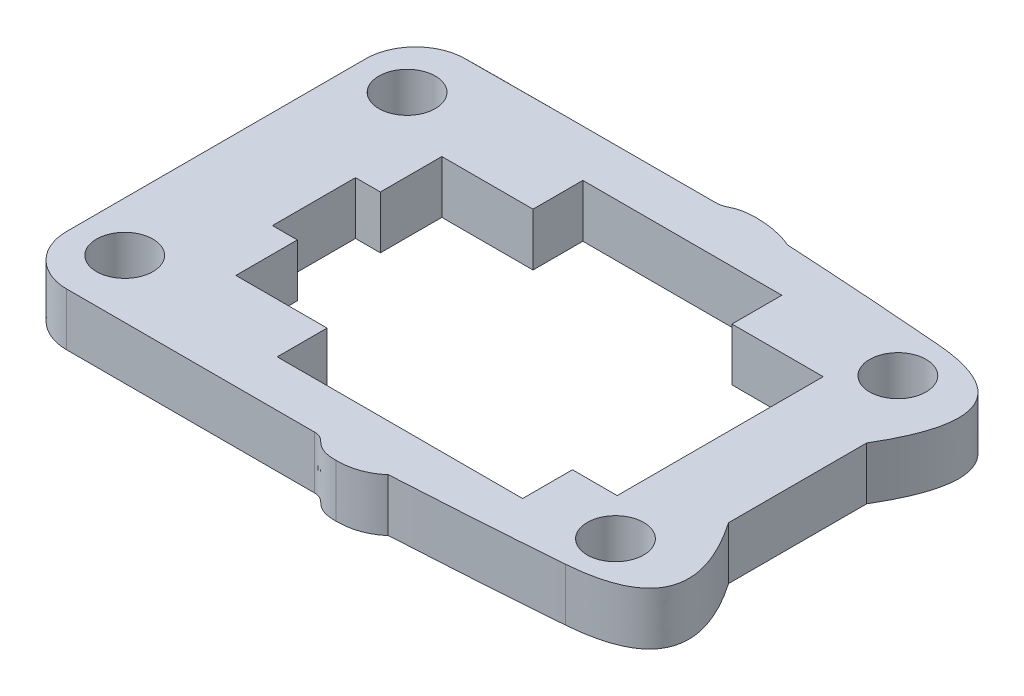
SolidWorks part; units mm, degrees
material "Acrylic (Medium-high impact)"
ref_plane "Front Plane" through (0, 0, 0) normal (0, 0, 1) x (1, 0, 0)
ref_plane "Top Plane" through (0, 0, 0) normal (0, 1, 0) x (1, 0, 0)
ref_plane "Right Plane" through (0, 0, 0) normal (1, 0, 0) x (0, 0, -1)
sketch "Sketch1" plane through (0, 0, 0) normal (0, 1, 0) x (1, 0, 0)
  line L0 (-5.1419, -4.4237) -> (-5.1419, -23.5635) construction
  line L1 (24.4058, -21.4242) -> (-7.2594, -21.4242) construction
  line L25 (-8.1366, -21.9243) -> (-8.1366, -3.9237)
  line L26 (26.9756, -8.8678) -> (26.9756, -17.1873)
  line L27 (-2.247, -15.4242) -> (-0.7496, -15.4242)
  line L28 (-0.7496, -15.4242) -> (-0.7496, -19.1243)
  line L29 (-0.7496, -19.1243) -> (4.7404, -19.1243)
  line L30 (4.7404, -19.1243) -> (4.7404, -22.1242)
  line L31 (4.7404, -22.1242) -> (19.5144, -22.1242)
  line L32 (19.5144, -22.1242) -> (19.5144, -19.1243)
  line L33 (19.5144, -19.1243) -> (22.2095, -19.1243)
  line L34 (22.2095, -19.1243) -> (22.2095, -6.7239)
  line L35 (22.2095, -6.7239) -> (16.7193, -6.7239)
  line L36 (16.7193, -6.7239) -> (16.7193, -3.7237)
  line L37 (16.7193, -3.7237) -> (4.7404, -3.7237)
  line L38 (4.7404, -3.7237) -> (4.7404, -6.7239)
  line L39 (4.7404, -6.7239) -> (-0.7496, -6.7239)
  line L40 (-0.7496, -6.7239) -> (-0.7496, -10.424)
  line L41 (-0.7496, -10.424) -> (-2.247, -10.424)
  line L42 (-2.247, -10.424) -> (-2.247, -15.4242)
  circle A0 centre (-5.1419, -4.4237) radius 1.7
  circle A1 centre (24.4058, -4.4237) radius 1.7
  circle A2 centre (-5.1419, -21.4242) radius 1.7
  circle A3 centre (24.4058, -21.4242) radius 1.7
  spline S9 degree 3 poles (-8.1366, -3.9237) (-8.1366, -3.1281) (-7.821, -2.365) (-7.2594, -1.8022) knots 1 1 1 1 2 2 2 2
  spline S10 degree 3 poles (-7.2594, -1.8022) (-6.6977, -1.2396) (-5.9362, -0.9236) (-5.1419, -0.9236) knots 2 2 2 2 3 3 3 3
  spline S11 degree 3 poles (-5.1419, -0.9236) (-5.1548, -0.903) (4.1658, -0.8787) (9.8792, -0.888) knots 3 3 3 3 4 4 4 4
  spline S12 degree 3 poles (9.8792, -0.888) (10.625, -0.8893) (10.5642, -0.4517) (11.9066, -0.4517) knots 4 4 4 4 5 5 5 5
  spline S13 degree 3 poles (11.9066, -0.4517) (13.316, -0.4517) (14.2148, -0.9091) (14.2236, -0.9236) knots 5 5 5 5 6 6 6 6
  spline S14 degree 2 poles (14.2236, -0.9236) (19.2567, -1.2064) (23.9716, -1.5887) knots 6 6 6 7 7 7
  spline S15 degree 2 poles (23.9716, -1.5887) (30.9955, -2.1584) (26.9756, -8.8678) knots 7 7 7 8 8 8
  spline S16 degree 2 poles (26.9756, -17.1873) (31.4427, -23.6896) (24.2317, -24.2591) knots 9 9 9 10 10 10
  spline S17 degree 2 poles (24.2317, -24.2591) (19.3908, -24.6415) (14.2236, -24.9242) knots 10 10 10 11 11 11
  spline S18 degree 2 poles (14.2236, -24.9242) (13.2977, -25.7529) (11.9066, -25.7529) knots 11 11 11 12 12 12
  spline S19 degree 3 poles (11.9066, -25.7529) (10.3986, -25.7529) (10.59, -24.9242) (9.7912, -24.9242) knots 12 12 12 12 13 13 13 13
  spline S20 degree 2 poles (9.7912, -24.9242) (4.0745, -24.9242) (-5.1419, -24.9242) knots 13 13 13 14 14 14
  spline S21 degree 3 poles (-5.1419, -24.9242) (-5.9362, -24.9242) (-6.6977, -24.6083) (-7.2594, -24.0457) knots 14 14 14 14 15 15 15 15
  spline S22 degree 3 poles (-7.2594, -24.0457) (-7.821, -23.4831) (-8.1366, -22.7198) (-8.1366, -21.9243) knots 15 15 15 15 16 16 16 16
  point P0 (-5.1419, -4.4237)
  point P1 (24.4058, -4.4237)
  point P2 (24.4058, -21.4242)
  dimension "D1" = 3.4
extrude "Boss-Extrude1" add sketch "Sketch1" along normal blind 3.175
